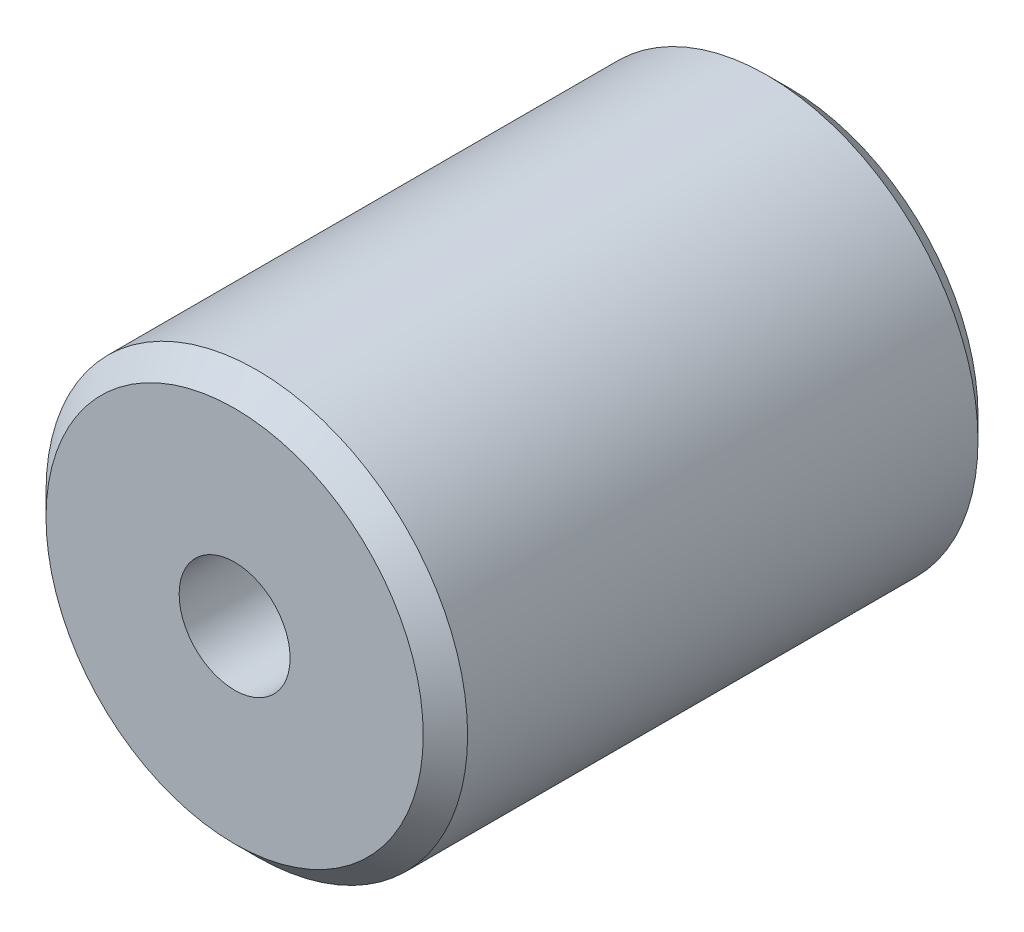
SolidWorks part; units mm, degrees
ref_plane "前视基准面" through (0, 0, 0) normal (0, 0, 1) x (1, 0, 0)
ref_plane "上视基准面" through (0, 0, 0) normal (0, 1, 0) x (1, 0, 0)
ref_plane "右视基准面" through (0, 0, 0) normal (1, 0, 0) x (0, 0, -1)
sketch "草图1" plane through (0, 0, 0) normal (0, 0, 1) x (1, 0, 0)
  circle A0 centre (0, 0) radius 9.5
  circle A1 centre (0, 0) radius 2.5
  dimension "D1" = 19
  dimension "D2" = 5
extrude "凸台-拉伸1" add sketch "草图1" along normal blind 25
chamfer "倒角1" distance 1 angle 45 2 edges at (9.5, 0, 0) (9.5, 0, 25)
sketch "草图2" plane through (0, 0, 0) normal (0, 0, -1) x (-1, 0, 0)
  circle A0 centre (0, 0) radius 4
  dimension "D1" = 8
extrude "切除-拉伸1" cut sketch "草图2" against normal blind 18
